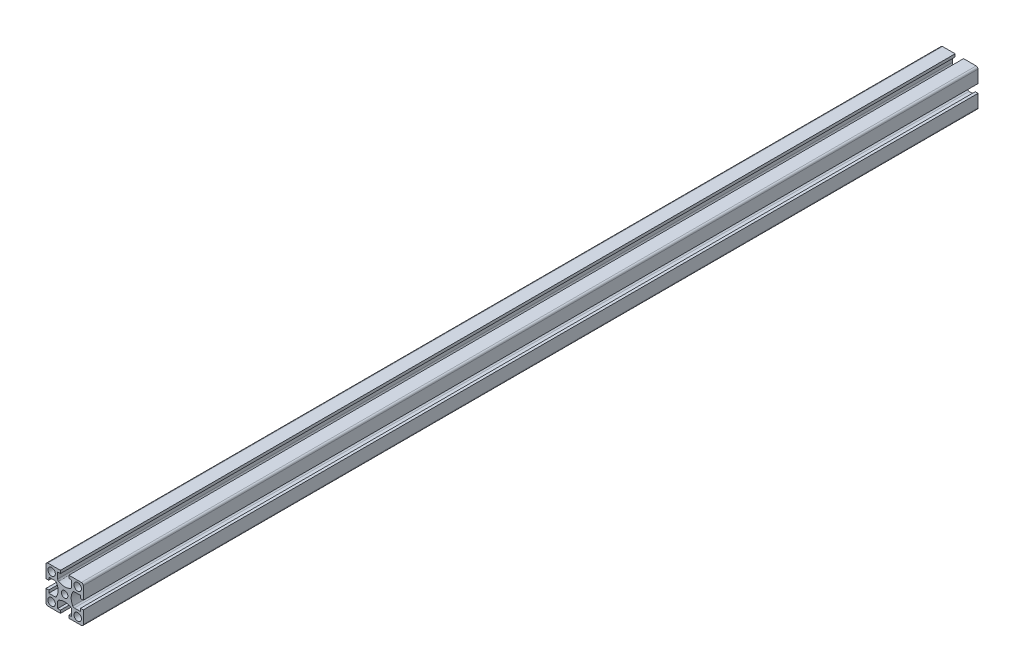
SolidWorks part; units mm, degrees
ref_plane "Front Plane" through (0, 0, 0) normal (0, 0, 1) x (1, 0, 0)
ref_plane "Top Plane" through (0, 0, 0) normal (0, 1, 0) x (1, 0, 0)
ref_plane "Right Plane" through (0, 0, 0) normal (1, 0, 0) x (0, 0, -1)
sketch "Sketch1" plane through (0, 0, 0) normal (0, 0, 1) x (1, 0, 0)
  line L64 (-20, 18) -> (-20, 4.5)
  line L65 (-20, 4.5) -> (-17, 4.5)
  line L66 (-17, 4.5) -> (-17, 7.5)
  line L67 (-17, 7.5) -> (-10.4737, 7.5)
  line L68 (-10.4737, -7.5) -> (-17, -7.5)
  line L69 (-17, -7.5) -> (-17, -4.5)
  line L70 (-17, -4.5) -> (-20, -4.5)
  line L71 (-20, -4.5) -> (-20, -18)
  line L72 (-18, -20) -> (-4.5, -20)
  line L73 (-4.5, -20) -> (-4.5, -17)
  line L74 (-4.5, -17) -> (-7.5, -17)
  line L75 (-7.5, -17) -> (-7.5, -10.4737)
  line L76 (7.5, -10.4737) -> (7.5, -17)
  line L77 (7.5, -17) -> (4.5, -17)
  line L78 (4.5, -17) -> (4.5, -20)
  line L79 (4.5, -20) -> (18, -20)
  line L80 (20, -18) -> (20, -4.5)
  line L81 (20, -4.5) -> (17, -4.5)
  line L82 (17, -4.5) -> (17, -7.5)
  line L83 (17, -7.5) -> (10.4737, -7.5)
  line L84 (10.4737, 7.5) -> (17, 7.5)
  line L85 (17, 7.5) -> (17, 4.5)
  line L86 (17, 4.5) -> (20, 4.5)
  line L87 (20, 4.5) -> (20, 18)
  line L88 (18, 20) -> (4.5, 20)
  line L89 (4.5, 20) -> (4.5, 17)
  line L90 (4.5, 17) -> (7.5, 17)
  line L91 (7.5, 17) -> (7.5, 10.4737)
  line L92 (-7.5, 10.4737) -> (-7.5, 17)
  line L93 (-7.5, 17) -> (-4.5, 17)
  line L94 (-4.5, 17) -> (-4.5, 20)
  line L95 (-4.5, 20) -> (-18, 20)
  circle A5 centre (-14, -14) radius 4
  circle A6 centre (14, -14) radius 4
  circle A7 centre (14, 14) radius 4
  circle A8 centre (0, 0) radius 3.5
  circle A9 centre (-14, 14) radius 4
  arc A32 (-18, 20) -> (-20, 18) centre (-18, 18) ccw
  arc A33 (-8.7417, 6.5) -> (-10.4737, 7.5) centre (-10.4737, 5.5) ccw
  arc A34 (-8.7417, -6.5) -> (-8.7417, 6.5) centre (-20, 0) ccw
  arc A35 (-10.4737, -7.5) -> (-8.7417, -6.5) centre (-10.4737, -5.5) ccw
  arc A36 (-20, -18) -> (-18, -20) centre (-18, -18) ccw
  arc A37 (-6.5, -8.7417) -> (-7.5, -10.4737) centre (-5.5, -10.4737) ccw
  arc A38 (6.5, -8.7417) -> (-6.5, -8.7417) centre (0, -20) ccw
  arc A39 (7.5, -10.4737) -> (6.5, -8.7417) centre (5.5, -10.4737) ccw
  arc A40 (18, -20) -> (20, -18) centre (18, -18) ccw
  arc A41 (8.7417, -6.5) -> (10.4737, -7.5) centre (10.4737, -5.5) ccw
  arc A42 (8.7417, 6.5) -> (8.7417, -6.5) centre (20, 0) ccw
  arc A43 (10.4737, 7.5) -> (8.7417, 6.5) centre (10.4737, 5.5) ccw
  arc A44 (20, 18) -> (18, 20) centre (18, 18) ccw
  arc A45 (6.5, 8.7417) -> (7.5, 10.4737) centre (5.5, 10.4737) ccw
  arc A46 (-6.5, 8.7417) -> (6.5, 8.7417) centre (0, 20) ccw
  arc A47 (-7.5, 10.4737) -> (-6.5, 8.7417) centre (-5.5, 10.4737) ccw
extrude "Boss-Extrude1" add sketch "Sketch1" along normal blind 960
